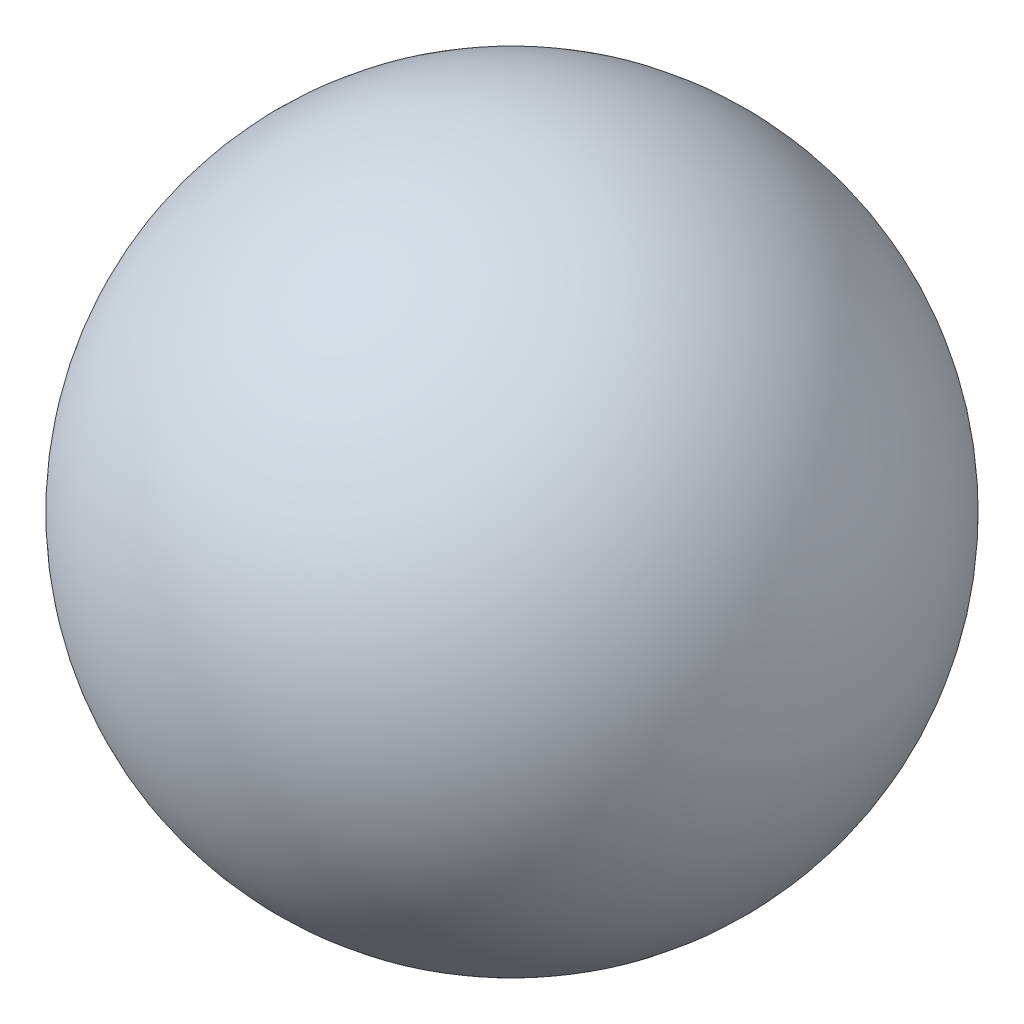
SolidWorks part; units mm, degrees
material "6061 Alloy"
ref_plane "Front Plane" through (0, 0, 0) normal (0, 0, 1) x (1, 0, 0)
ref_plane "Top Plane" through (0, 0, 0) normal (0, 1, 0) x (1, 0, 0)
ref_plane "Right Plane" through (0, 0, 0) normal (1, 0, 0) x (0, 0, -1)
sketch "Sketch2" plane through (0, 0, 0) normal (0, 0, 1) x (1, 0, 0)
  line L0 (0, 0) -> (0, 19.05)
  arc A0 (0, 19.05) -> (0, 0) centre (0, 9.525) cw
  dimension "D1" = 19.05
revolve "Revolve1" add sketch "Sketch2" angle 360 about L0
